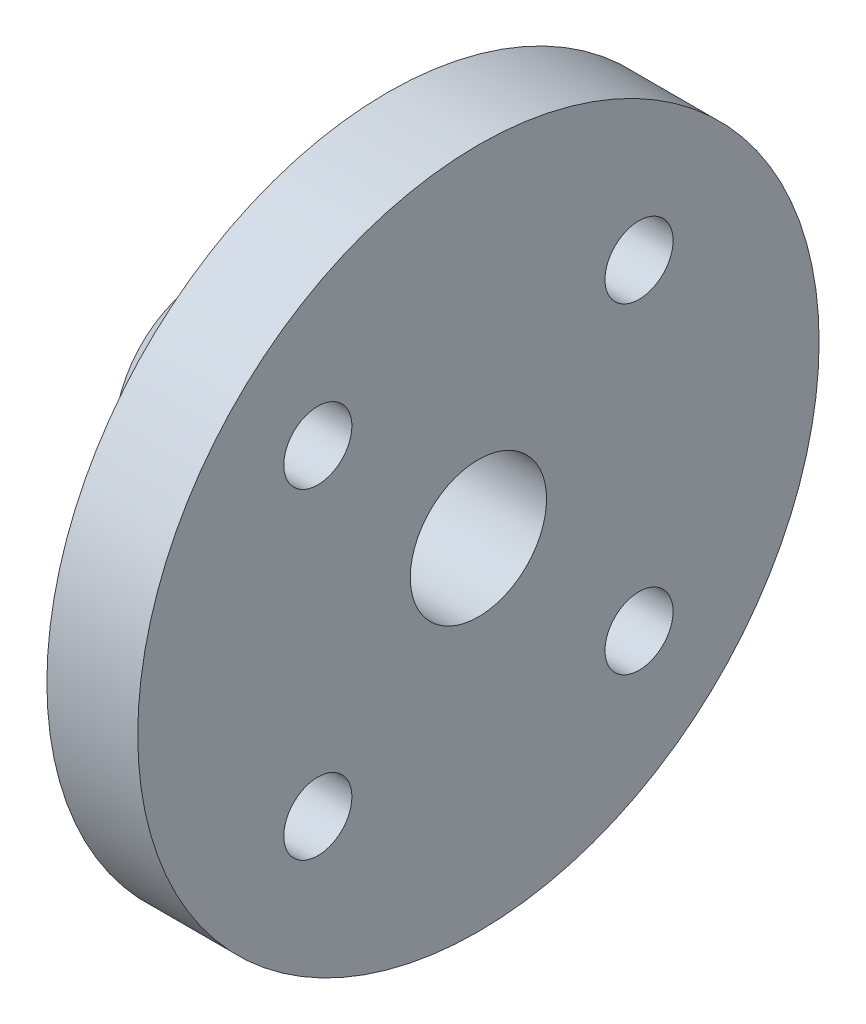
SolidWorks part; units mm, degrees
material "7075-T6, Plate (SS)"
ref_plane "Front Plane" through (0, 0, 0) normal (0, 0, 1) x (1, 0, 0)
ref_plane "Top Plane" through (0, 0, 0) normal (0, 1, 0) x (1, 0, 0)
ref_plane "Right Plane" through (0, 0, 0) normal (1, 0, 0) x (0, 0, -1)
sketch "Sketch1" plane through (0, 0, 0) normal (0, 0, 1) x (1, 0, 0)
  line L0 (0, 0) -> (20.2049, 0) construction
  line L1 (0, 0) -> (0, 20.0131) construction
  line L2 (12, 3) -> (12, 15)
  line L3 (12, 15) -> (8, 15)
  line L4 (8, 15) -> (8, 5)
  line L5 (8, 5) -> (1, 5)
  line L6 (0, 4) -> (0, 3)
  line L7 (0, 3) -> (12, 3)
  line L8 (1, 5) -> (0, 4)
  point P9 (0, 5)
  dimension "D1" = 30
  dimension "D2" = 10
  dimension "D3" = 6
  dimension "D4" = 4
  dimension "D5" = 8
revolve "Revolve1" add sketch "Sketch1" angle 360 about L0
sketch "Sketch2" plane through (0, 0, 0) normal (0, 1, 0) x (1, 0, 0)
  line L1 (8, 15) -> (8, -15) construction
  circle A0 centre (4, 0) radius 1.5
  dimension "D2" = 3
  dimension "D1" = 4
extrude "Cut-Extrude1" cut sketch "Sketch2" against normal blind 5
sketch "Sketch3" plane through (12, 0, 0) normal (1, 0, 0) x (0, 0, -1)
  line L0 (-7.0711, 7.0711) -> (0, 0) construction
  line L1 (0, 0) -> (7.0711, 7.0711) construction
  line L2 (0, 0) -> (0, 10) construction
  line L3 (0, 0) -> (10, 0) construction
  circle A0 centre (0, 0) radius 10 construction
  circle A1 centre (-7.0711, 7.0711) radius 1.5
  circle A2 centre (7.0711, 7.0711) radius 1.5
  circle A3 centre (7.0711, -7.0711) radius 1.5
  circle A4 centre (-7.0711, -7.0711) radius 1.5
  point P14 (0, 0)
  dimension "D1" = 20
  dimension "D2" = 3
  dimension "D4" = 45
  dimension "D3" = 4
extrude "Cut-Extrude2" cut sketch "Sketch3" against normal through all
